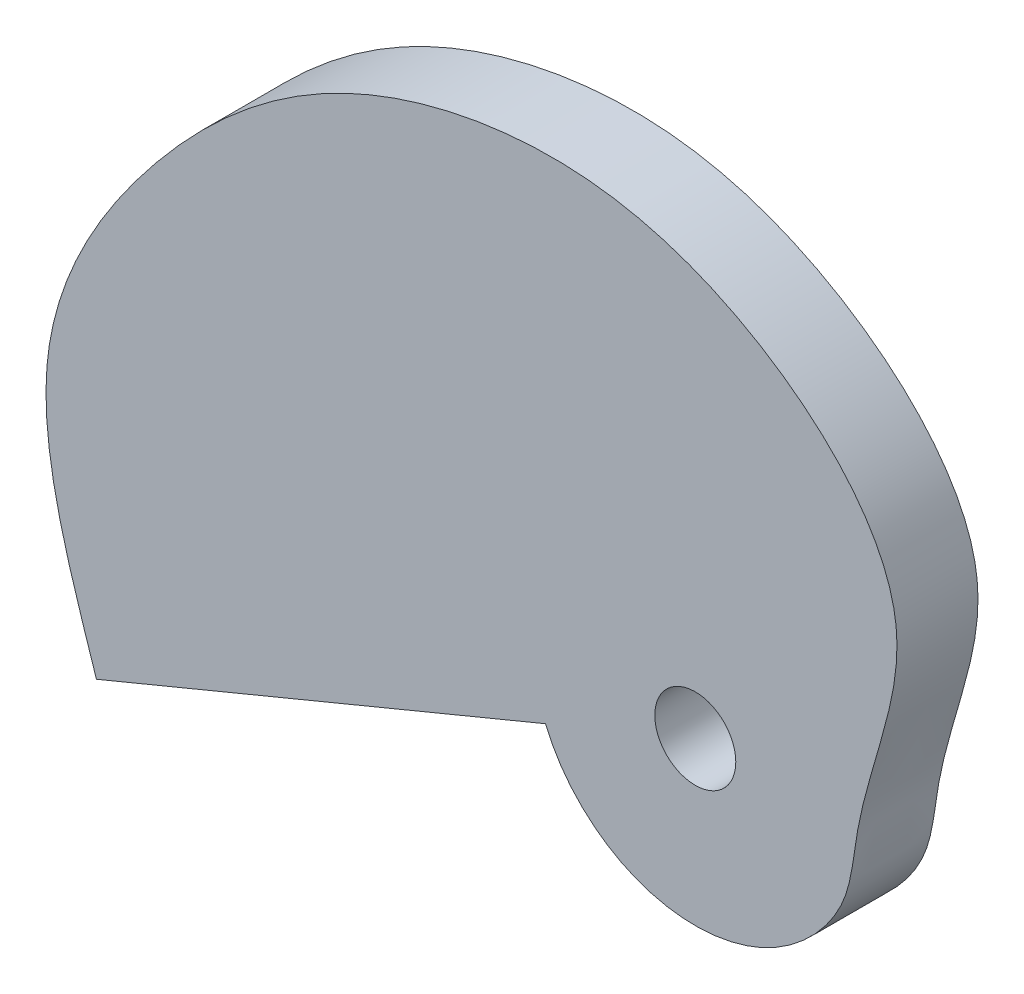
SolidWorks part; units mm, degrees
ref_plane "Front Plane" through (0, 0, 0) normal (0, 0, 1) x (1, 0, 0)
ref_plane "Top Plane" through (0, 0, 0) normal (0, 1, 0) x (1, 0, 0)
ref_plane "Right Plane" through (0, 0, 0) normal (1, 0, 0) x (0, 0, -1)
sketch "Sketch1" plane through (0, 0, 0) normal (0, 0, 1) x (1, 0, 0)
  line L0 (0, 0) -> (12.7, 0) construction
  line L1 (0, 0) -> (-50.8, 0) construction
  line L2 (0, 0) -> (0, 31.75) construction
  line L3 (0, 0) -> (15.7154, 15.7154) construction
  line L4 (0, 0) -> (-29.1858, 29.1858) construction
  line L5 (0, 0) -> (-13.9727, 33.7332) construction
  line L6 (0, 0) -> (-42.5331, 17.6178) construction
  line L7 (0, 0) -> (11.7333, -4.8601) construction
  line L8 (0, 0) -> (-49.8239, -9.9106) construction
  line L9 (0, 0) -> (-46.9331, -19.4403) construction
  line L10 (0, 0) -> (8.9803, -8.9803) construction
  line L11 (0, 0) -> (4.8601, -11.7333) construction
  line L12 (0, 0) -> (0, -12.7) construction
  line L13 (0, 0) -> (-4.8601, -11.7333) construction
  line L14 (0, 0) -> (-8.9803, -8.9803) construction
  line L15 (0, 0) -> (-11.7333, -4.8601) construction
  line L16 (-11.7333, -4.8601) -> (-46.9331, -19.4403)
  circle A1 centre (0, 0) radius 3.175
  spline S0 degree 3 poles (-11.7333, -4.8601) (-10.4875, -7.957) (-6.6494, -11.7104) (-0.0021, -13.0302) (4.9961, -12.0388) (9.1781, -9.2141) (12.1729, -4.9864) (12.7953, 3.7039) (20.1377, 18.2935) (2.7317, 32.7215) (-14.5209, 34.7131) (-30.4318, 29.9721) (-43.5439, 17.9029) (-53.8138, 0.1992) (-48.9004, -13.4177) (-46.9331, -19.4403) knots 0 0 0 0 0.061874 0.092812 0.123749 0.154686 0.185623 0.216561 0.316466 0.456638 0.544748 0.64388 0.754153 0.875652 1 1 1 1
  dimension "D1" = 12.7
  dimension "D12" = 11.25
  dimension "D16" = 6.35
  dimension "D17" = 22.5
  dimension "D2" = 50.8
  dimension "D3" = 31.75
  dimension "D4" = 45
  dimension "D5" = 22.225
  dimension "D6" = 45
  dimension "D7" = 41.275
  dimension "D8" = 22.5
  dimension "D9" = 36.5125
  dimension "D10" = 22.5
  dimension "D11" = 46.0375
  dimension "D13" = 11.25
  dimension "D14" = 22.5
  dimension "D15" = 22.5
  dimension "D18" = 22.5
  dimension "D19" = 22.5
  dimension "D20" = 22.5
extrude "Boss-Extrude1" add sketch "Sketch1" along normal blind 6.35
